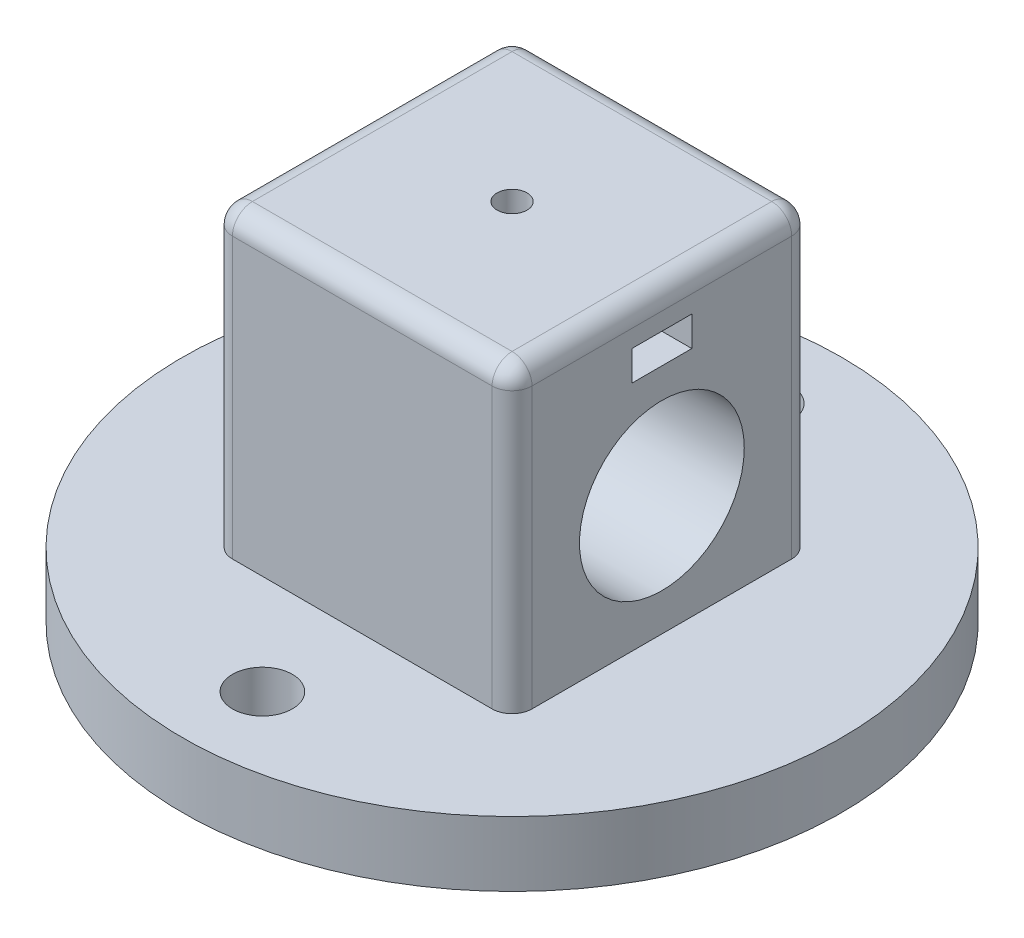
SolidWorks part; units mm, degrees
ref_plane "Alzado" through (0, 0, 0) normal (0, 0, 1) x (1, 0, 0)
ref_plane "Planta" through (0, 0, 0) normal (0, 1, 0) x (1, 0, 0)
ref_plane "Vista lateral" through (0, 0, 0) normal (1, 0, 0) x (0, 0, -1)
sketch "Sketch1" plane through (0, 0, 0) normal (0, 1, 0) x (1, 0, 0)
  line L0 (0, 33) -> (0, 28)
  line L1 (0, 28) -> (0, 22)
  line L2 (-33, 0) -> (-25, 0)
  line L3 (33, 0) -> (25, 0)
  line L4 (0, -33) -> (0, -25)
  circle A0 centre (0, 0) radius 33
  circle A1 centre (0, 25) radius 3
  circle A2 centre (-25, 0) radius 3
  circle A3 centre (25, 0) radius 3
  circle A4 centre (0, -25) radius 3
  dimension "D1" = 66
  dimension "D5" = 6
  dimension "D7" = 6
  dimension "D9" = 6
  dimension "D2" = 5
  dimension "D3" = 6
  dimension "D4" = 8
  dimension "D6" = 8
  dimension "D8" = 8
extrude "Boss-Extrude2" add sketch "Sketch1" along normal blind 6.5 contours A0
sketch "Sketch3" plane through (0, 6.5, 0) normal (0, 1, 0) x (1, 0, 0)
sketch "Sketch4" plane through (0, 6.5, 0) normal (0, 1, 0) x (1, 0, 0)
  line L1 (0, 33) -> (0, 25)
  line L3 (0, -33) -> (0, -25)
  circle A0 centre (0, 0) radius 33 construction
  circle A2 centre (0, 25) radius 3
  circle A4 centre (0, -25) radius 3
  dimension "D3" = 8
  dimension "D4" = 6
  dimension "D8" = 6
  dimension "D7" = 8
extrude "Cut-Extrude1" cut sketch "Sketch4" against normal blind 6.5
sketch "Sketch5" plane through (0, 6.5, 0) normal (0, 1, 0) x (1, 0, 0)
  line L0 (0, 0) -> (15, 0)
  line L1 (0, 0) -> (-15, 0)
  line L2 (-15, 0) -> (-15, -15)
  line L4 (-15, -15) -> (15, -15)
  line L5 (-15, -15) -> (-15, 15)
  line L6 (-15, 15) -> (15, 15)
  line L7 (15, -15) -> (15, 15)
  dimension "D1" = 15
  dimension "D2" = 15
  dimension "D3" = 15
  dimension "D4" = 30
  dimension "D5" = 30
extrude "Boss-Extrude3" add sketch "Sketch5" along normal blind 30 contours L4 L7 L0 L1 L2 | L0 L7 L6 L5 L1
sketch "Sketch6" plane through (15, 0, 0) normal (1, 0, 0) x (0, 0, -1)
  line L0 (0, 36.5) -> (0, 18.5)
  line L1 (-15, 36.5) -> (15, 36.5) construction
  circle A0 centre (0, 18.5) radius 8.25
  dimension "D2" = 16.5
  dimension "D1" = 18
extrude "Cut-Extrude2" cut sketch "Sketch6" against normal blind 30 contours A0
sketch "Sketch8" plane through (0, 36.5, 0) normal (0, 1, 0) x (1, 0, 0)
  line L0 (-15, 0) -> (0, 0)
  line L1 (-15, 15) -> (-15, -15) construction
  circle A0 centre (0, 0) radius 1.5
  dimension "D2" = 3
  dimension "D1" = 15
extrude "Cut-Extrude3" cut sketch "Sketch8" against normal blind 10
sketch "Sketch9" plane through (-15, 0, 0) normal (-1, 0, 0) x (0, 0, 1)
  line L0 (0, 36.5) -> (0, 32.75)
  line L1 (-15, 36.5) -> (15, 36.5) construction
  line L2 (0, 32.75) -> (-3, 32.75)
  line L4 (-3, 32.75) -> (3, 32.75)
  line L5 (-3, 32.75) -> (-3, 29.75)
  line L6 (-3, 29.75) -> (3, 29.75)
  line L7 (3, 32.75) -> (3, 29.75)
  dimension "D1" = 3.75
  dimension "D2" = 3
  dimension "D3" = 3
  dimension "D4" = 6
extrude "Cut-Extrude4" cut sketch "Sketch9" against normal blind 30 contours L7 L4 L2 L5 L6
fillet "Fillet12" radius 2 1 edges at (0, 36.5, -15)
fillet "Fillet13" radius 2 1 edges at (0, 36.5, 15)
fillet "Fillet14" radius 2 5 edges at (15, 20.5, -15) (15, 35.9142, -14.4142) (15, 20.5, 15) (15, 36.5, 0) (15, 35.9142, 14.4142)
fillet "Fillet15" radius 2 5 edges at (-15, 20.5, -15) (-15, 36.5, 0) (-15, 35.9142, -14.4142) (-15, 20.5, 15) (-15, 35.9142, 14.4142)
